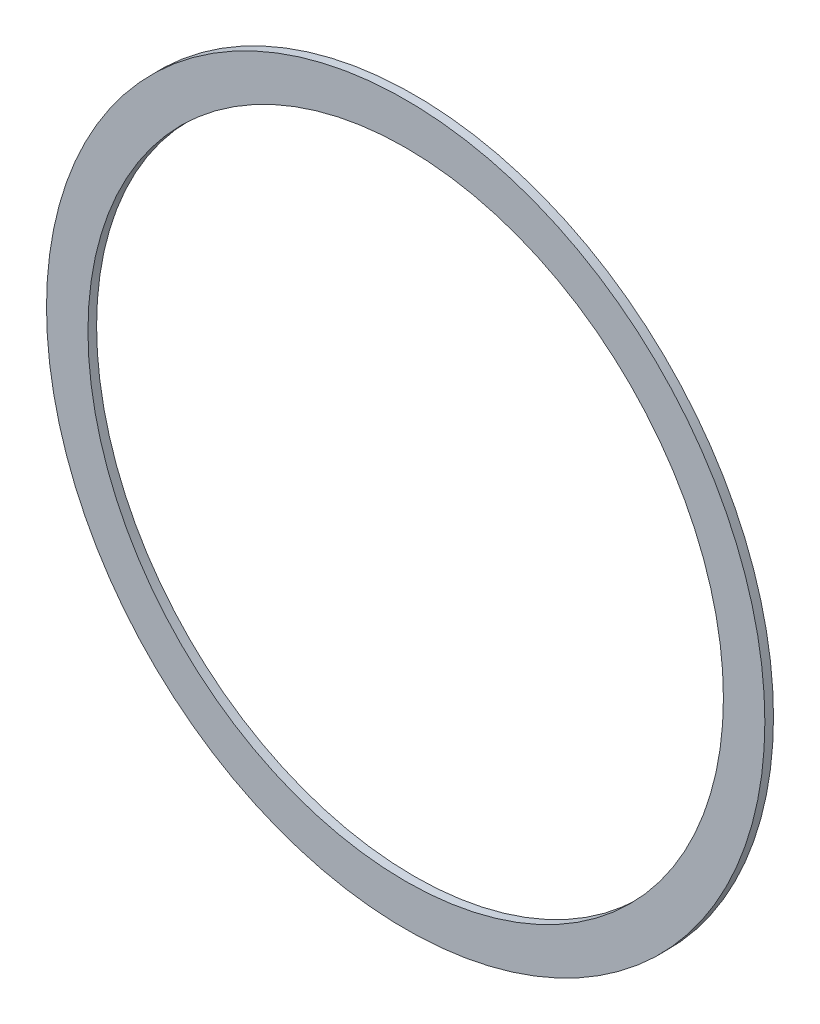
SolidWorks part; units mm, degrees
material "Balsa"
ref_plane "Front Plane" through (0, 0, 0) normal (0, 0, 1) x (1, 0, 0)
ref_plane "Top Plane" through (0, 0, 0) normal (0, 1, 0) x (1, 0, 0)
ref_plane "Right Plane" through (0, 0, 0) normal (1, 0, 0) x (0, 0, -1)
sketch "Sketch2" plane through (0, 0, 0) normal (0, 0, 1) x (1, 0, 0)
  line L0 (0, 0) -> (0, 236.6718) construction
  line L1 (-1.651, 128.5137) -> (-1.651, 121.4017) construction
  line L3 (1.651, 128.5137) -> (1.651, 121.4017) construction
  line L4 (-1.651, 121.4017) -> (1.651, 121.4017) construction
  line L5 (-136.2076, -77.8947) -> (0.0002, 0.7357) construction
  line L6 (-136.2076, -77.8947) -> (0.0002, 0.7357) construction
  line L7 (136.2041, -77.9016) -> (0.0002, 0.7357) construction
  line L8 (136.2041, -77.9016) -> (0.0002, 0.7357) construction
  line L9 (-116.9771, -64.8869) -> (-110.0184, -60.8698) construction
  line L10 (-115.4068, -67.7931) -> (-108.3675, -63.7295) construction
  line L11 (-110.0184, -60.8698) -> (-108.3675, -63.7295) construction
  line L12 (-117.5533, -65.2196) -> (-116.9771, -64.8869) construction
  line L13 (-115.9024, -68.0792) -> (-115.4068, -67.7931) construction
  line L14 (115.4068, -67.7931) -> (109.2475, -64.2371) construction
  line L15 (110.8985, -61.3775) -> (109.2475, -64.2371) construction
  line L16 (116.9771, -64.8869) -> (110.8985, -61.3775) construction
  arc A0 (-1.651, 128.5137) -> (-116.9771, -64.8869) centre (0, -3.556) ccw
  arc A1 (0.0665, 128.1531) -> (63.0696, -118.8475) centre (0, -3.3993) ccw construction
  circle A2 centre (0, -3.556) radius 116.84
  arc A3 (63.0696, -118.8475) -> (0.0665, 128.1531) centre (0, -3.3993) ccw construction
  arc A4 (0, 128.524) -> (-1.651, 128.5137) centre (0, -3.556) ccw
  circle A5 centre (0, -3.556) radius 132.08 construction
  arc A6 (1.651, 128.5137) -> (0, 128.524) centre (0, -3.556) ccw
  arc A7 (-116.9771, -64.8869) -> (-116.2009, -66.3452) centre (0, -3.556) ccw
  arc A8 (-115.4068, -67.7931) -> (115.4068, -67.7931) centre (0, -3.556) ccw
  arc A9 (-116.2009, -66.3452) -> (-115.4068, -67.7931) centre (0, -3.556) ccw
  arc A10 (115.4068, -67.7931) -> (116.1978, -66.3509) centre (0, -3.556) ccw
  arc A11 (116.9771, -64.8869) -> (1.651, 128.5137) centre (0, -3.556) ccw
  arc A12 (116.1978, -66.3509) -> (116.9771, -64.8869) centre (0, -3.556) ccw
  point P24 (-115.4068, -67.7931)
  dimension "D1" = 3.556
  dimension "D3" = 264.16
  dimension "D2" = 15.24
  dimension "D4" = 3.302
  dimension "D5" = 7.112
  dimension "D6" = 3.302
  dimension "D7" = 8.128
  dimension "D8" = 7.076
extrude "Boss-Extrude1" add sketch "Sketch2" along normal mid plane 3.175
